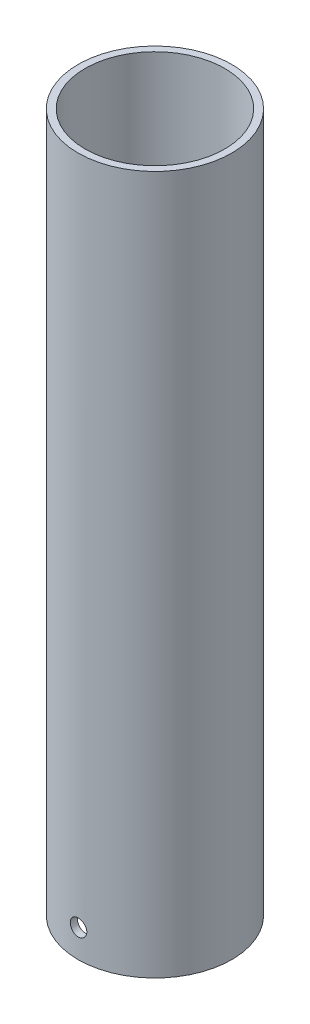
SolidWorks part; units mm, degrees
ref_plane "Front Plane" through (0, 0, 0) normal (0, 0, 1) x (1, 0, 0)
ref_plane "Top Plane" through (0, 0, 0) normal (0, 1, 0) x (1, 0, 0)
ref_plane "Right Plane" through (0, 0, 0) normal (1, 0, 0) x (0, 0, -1)
sketch "Sketch1" plane through (0, 0, 0) normal (0, 1, 0) x (1, 0, 0)
  circle A0 centre (0, 0) radius 50
  circle A1 centre (0, 0) radius 55
  dimension "D1" = 5
  dimension "D2" = 100
extrude "Boss-Extrude2" add sketch "Sketch1" against normal blind 500
ref_plane "Drain hole level" through (0, -480, 0) normal (0, 1, 0) x (1, 0, 0)
ref_plane "Parallel to Mantle" through (0, 0, 55) normal (0, 0, 1) x (1, 0, 0)
hole_wizard "G1/4 Tapped Hole1" positions "Sketch4" profile "Sketch6" tap size "G1/4" standard "ISO"
sketch "Sketch4" plane through (0, 0, 55) normal (0, 0, 1) x (1, 0, 0)
  line L0 (0, -500) -> (0, 0) construction
  line L2 (-55, -500) -> (55, -500) construction
  line L3 (60.5, -480) -> (-60.5, -480) construction
  point P0 (0, -480)
cosmetic thread "Hole Thread1" parameters "D1"=5.3493, "D2"=13.157
sketch "Sketch6" plane through (0, -480, 55) normal (1, 0, 0) x (0, -1, 0)
  line L0 (0, 0) -> (0, 33.8651)
  line L1 (0, 33.8651) -> (5.9, 30.32)
  line L2 (5.9, 30.32) -> (5.9, 0)
  line L5 (5.9, 0) -> (0, 0)
  line L10 (0, 33.8651) -> (-5.9, 30.32) construction
  line L11 (0, -6.35) -> (0, 107.95) construction
  dimension "Tap Drill Dia." = 11.8
  dimension "Tap Drill Depth" = 30.32
  dimension "Drill Angle" = 118
